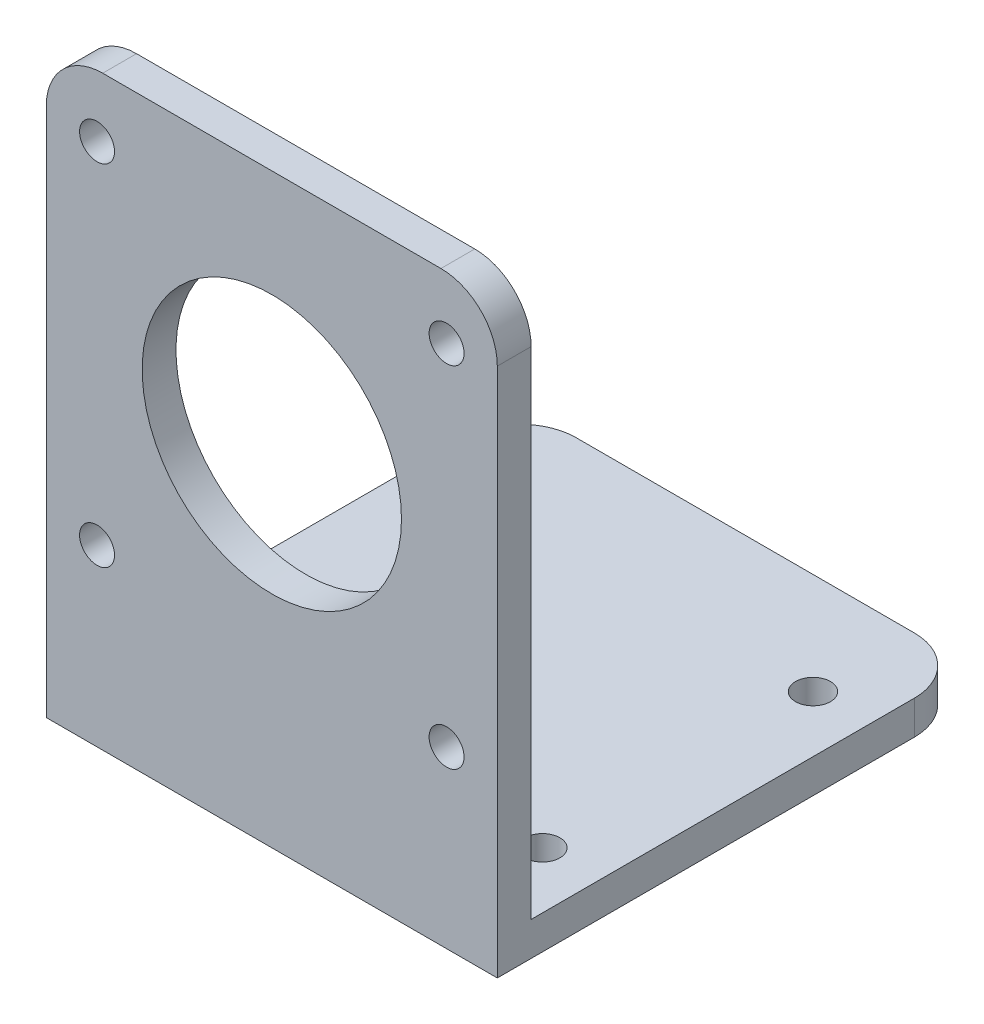
SolidWorks part; units mm, degrees
ref_plane "前视基准面" through (0, 0, 0) normal (0, 0, 1) x (1, 0, 0)
ref_plane "上视基准面" through (0, 0, 0) normal (0, 1, 0) x (1, 0, 0)
ref_plane "右视基准面" through (0, 0, 0) normal (1, 0, 0) x (0, 0, -1)
other "Configuration Table"
sketch "草图1" plane through (0, 0, 0) normal (1, 0, 0) x (0, 0, -1)
  line L0 (0, 0) -> (0, 52)
  line L1 (0, 52) -> (3, 52)
  line L2 (3, 52) -> (3, 3)
  line L3 (3, 3) -> (42, 3)
  line L4 (42, 3) -> (42, 0)
  line L5 (42, 0) -> (0, 0)
  dimension "D1" = 3
  dimension "D2" = 3
  dimension "D3" = 52
  dimension "D4" = 42
extrude "凸台-拉伸1" add sketch "草图1" against normal mid plane 40
sketch "草图2" plane through (0, 0, 0) normal (0, 0, 1) x (1, 0, 0)
  line L0 (0, 66.1556) -> (0, -5.8807) construction
  circle A0 centre (15.5, 46.5) radius 1.55
  circle A1 centre (15.5, 15.5) radius 1.55
  circle A2 centre (-15.5, 15.5) radius 1.55
  circle A3 centre (-15.5, 46.5) radius 1.55
  circle A4 centre (0, 31) radius 11.5
  point P13 (0, 0)
  point P14 (15.5, 15.5)
  point P15 (0, 0)
  dimension "D1" = 3.1
  dimension "D4" = 23
  dimension "D2" = 31
  dimension "D3" = 31
  dimension "D5" = 31
  dimension "D6" = 15.5
extrude "切除-拉伸1" cut sketch "草图2" against normal up to next
sketch "草图3" plane through (0, 0, 0) normal (0, 1, 0) x (1, 0, 0)
  line L0 (0, 75.0222) -> (0, -17.6362) construction
  circle A0 centre (15, 33) radius 1.55
  circle A1 centre (15, 9) radius 1.55
  circle A2 centre (-15, 9) radius 1.55
  circle A3 centre (-15, 33) radius 1.55
  point P11 (0, 0)
  dimension "D1" = 3.1
  dimension "D2" = 24
  dimension "D3" = 30
  dimension "D4" = 9
extrude "切除-拉伸2" cut sketch "草图3" along normal up to next
fillet "圆角1" radius 5 4 edges at (-20, 52, -1.5) (20, 52, -1.5) (20, 1.5, -42) (-20, 1.5, -42)
